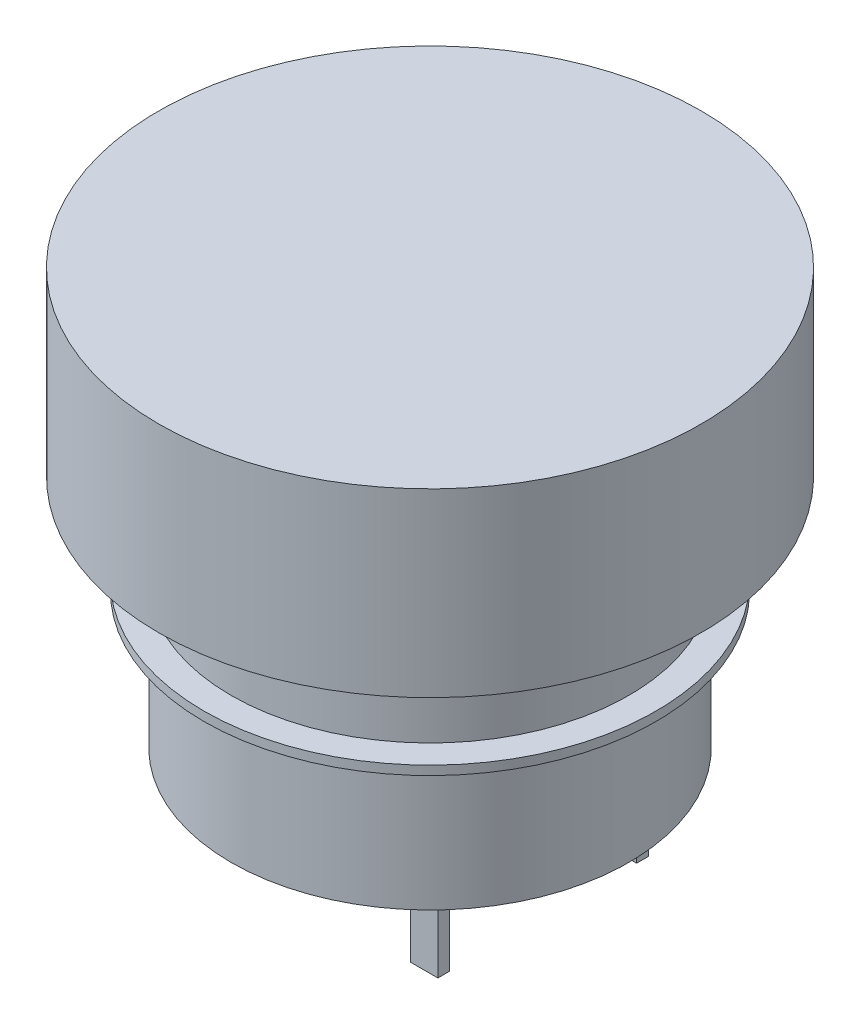
SolidWorks part; units mm, degrees
ref_plane "Plan de face" through (0, 0, 0) normal (0, 0, 1) x (1, 0, 0)
ref_plane "Plan de dessus" through (0, 0, 0) normal (0, 1, 0) x (1, 0, 0)
ref_plane "Plan de droite" through (0, 0, 0) normal (1, 0, 0) x (0, 0, -1)
sketch "Esquisse1" plane through (0, 0, 0) normal (0, 1, 0) x (1, 0, 0)
  circle A0 centre (0, 0) radius 22
extrude "Boss.-Extru.1" add sketch "Esquisse1" along normal blind 15
sketch "Esquisse2" plane through (0, 15, 0) normal (0, 1, 0) x (1, 0, 0)
  circle A0 centre (0, 0) radius 25
extrude "Boss.-Extru.2" add sketch "Esquisse2" along normal blind 1
sketch "Esquisse3" plane through (0, 16, 0) normal (0, 1, 0) x (1, 0, 0)
  circle A0 centre (0, 0) radius 22
extrude "Boss.-Extru.3" add sketch "Esquisse3" along normal blind 10
sketch "Esquisse4" plane through (0, 26, 0) normal (0, 1, 0) x (1, 0, 0)
  circle A0 centre (0, 0) radius 30
extrude "Boss.-Extru.4" add sketch "Esquisse4" along normal blind 20
sketch "Esquisse5" plane through (0, 0, 0) normal (0, -1, 0) x (1, 0, 0)
  line L0 (0, 0) -> (22, 0) construction
  line L1 (22, 0) -> (-22, 0) construction
  line L2 (-22, 0) -> (0, -22) construction
  line L3 (0, -22) -> (0, 22) construction
  line L4 (0, 22) -> (22, 0) construction
  line L5 (22, 0) -> (0, -22) construction
  line L6 (-22, 0) -> (0, 22) construction
  line L7 (-22, 22) -> (0, 22) construction
  line L12 (-22, 22) -> (22, -22) construction
  line L13 (-22, -22) -> (22, 22) construction
  line L15 (-12.5, 11.6301) -> (-9.5, 11.6301)
  line L16 (-12.5, 11.6301) -> (-12.5, 10.3699)
  line L17 (-12.5, 10.3699) -> (-9.5, 10.3699)
  line L18 (-9.5, 11.6301) -> (-9.5, 10.3699)
  line L19 (-12.5, 11.6301) -> (-9.5, 10.3699) construction
  line L20 (-12.5, 10.3699) -> (-9.5, 11.6301) construction
  line L21 (-12.5, -10.352) -> (-9.5, -10.352)
  line L22 (-12.5, -10.352) -> (-12.5, -11.648)
  line L23 (-12.5, -11.648) -> (-9.5, -11.648)
  line L24 (-9.5, -10.352) -> (-9.5, -11.648)
  line L25 (-12.5, -10.352) -> (-9.5, -11.648) construction
  line L26 (-12.5, -11.648) -> (-9.5, -10.352) construction
  line L27 (9.5, -10.352) -> (12.5, -10.352)
  line L28 (9.5, -10.352) -> (9.5, -11.648)
  line L29 (9.5, -11.648) -> (12.5, -11.648)
  line L30 (12.5, -10.352) -> (12.5, -11.648)
  line L31 (9.5, -10.352) -> (12.5, -11.648) construction
  line L32 (9.5, -11.648) -> (12.5, -10.352) construction
  line L33 (9.5, 11.6301) -> (12.5, 11.6301)
  line L34 (9.5, 11.6301) -> (9.5, 10.3699)
  line L35 (9.5, 10.3699) -> (12.5, 10.3699)
  line L36 (12.5, 11.6301) -> (12.5, 10.3699)
  line L37 (9.5, 11.6301) -> (12.5, 10.3699) construction
  line L38 (9.5, 10.3699) -> (12.5, 11.6301) construction
  circle A0 centre (0, 0) radius 22 construction
  point P13 (-11, 11)
  point P18 (-11, -11)
  point P23 (11, -11)
  point P28 (11, 11)
  dimension "D1" = 3
  dimension "D2" = 3
  dimension "D3" = 3
  dimension "D4" = 3
extrude "Boss.-Extru.5" add sketch "Esquisse5" along normal blind 10
